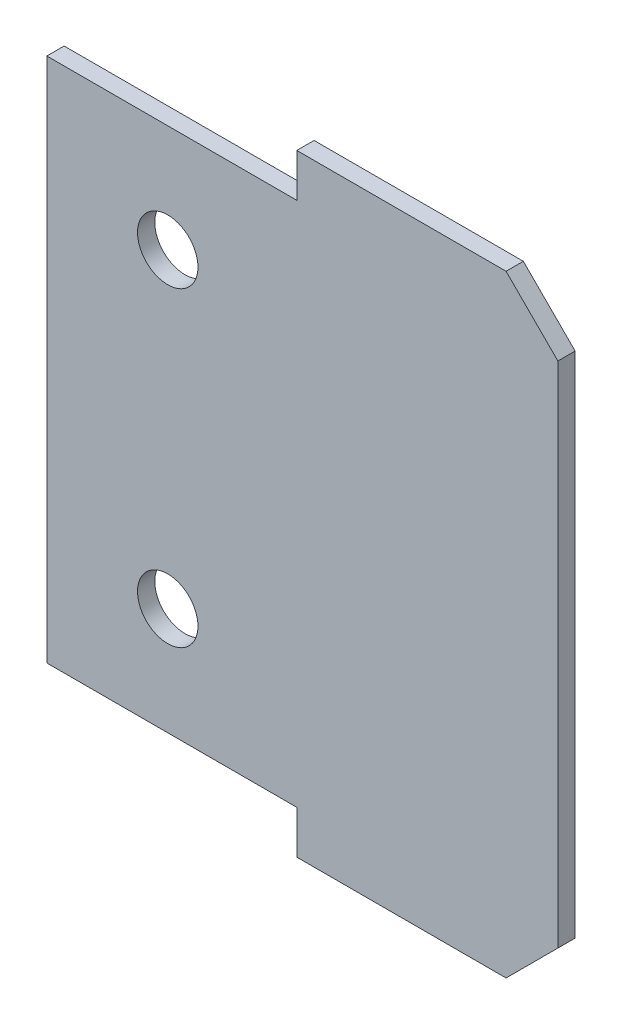
SolidWorks part; units mm, degrees
ref_plane "Front Plane" through (0, 0, 0) normal (0, 0, 1) x (1, 0, 0)
ref_plane "Top Plane" through (0, 0, 0) normal (0, 1, 0) x (1, 0, 0)
ref_plane "Right Plane" through (0, 0, 0) normal (1, 0, 0) x (0, 0, -1)
sketch "Sketch1" plane through (0, 0, 0) normal (0, 0, 1) x (1, 0, 0)
  line L0 (981.2098, 235.7406) -> (981.2098, 42.4466)
  line L1 (981.2098, 42.4466) -> (1073.1084, 42.4466)
  line L2 (1073.1084, 42.4466) -> (1073.1084, 26.5716)
  line L3 (1073.1084, 26.5716) -> (1150.0563, 26.5716)
  line L4 (1169.1063, 45.6216) -> (1169.1063, 232.5656)
  line L5 (1150.0563, 251.6156) -> (1073.1084, 251.6156)
  line L6 (1073.1084, 251.6156) -> (1073.1084, 235.7406)
  line L7 (1073.1084, 235.7406) -> (981.2098, 235.7406)
  line L8 (-1063.4902, 39.2716) -> (1070.1098, 39.2716) construction
  line L9 (1150.0563, 26.5716) -> (1169.1063, 45.6216)
  line L10 (1150.0563, 251.6156) -> (1169.1063, 232.5656)
  line L11 (1070.1098, 39.2716) -> (1070.1098, 238.9156) construction
  line L12 (1073.1084, 26.5716) -> (1071.6973, 26.5716) construction
  line L13 (981.2098, 139.0936) -> (1070.1098, 139.0936) construction
  line L14 (1070.1098, 238.9156) -> (1070.1098, 39.2716) construction
  line L15 (1025.6598, 196.2436) -> (1025.6598, 81.9436) construction
  line L16 (1150.0563, 251.6156) -> (1169.1063, 251.6156) construction
  line L17 (1169.1063, 251.6156) -> (1169.1063, 232.5656) construction
  line L18 (1169.1063, 45.6216) -> (1169.1063, 26.5716) construction
  line L19 (1169.1063, 26.5716) -> (1150.0563, 26.5716) construction
  line L20 (1169.1063, 39.2716) -> (1169.1063, 238.9156) construction
  circle A4 centre (1025.6598, 196.2436) radius 11.1125
  circle A5 centre (1025.6598, 81.9436) radius 11.1125
  point P30 (1025.6598, 139.0936)
  dimension "D4" = 22.225
  dimension "D1" = 3.175
  dimension "D2" = 88.9
  dimension "D3" = 1.4111
  dimension "D5" = 114.3
  dimension "D6" = 19.05
extrude "Boss-Extrude1" add sketch "Sketch1" along normal blind 6.35
